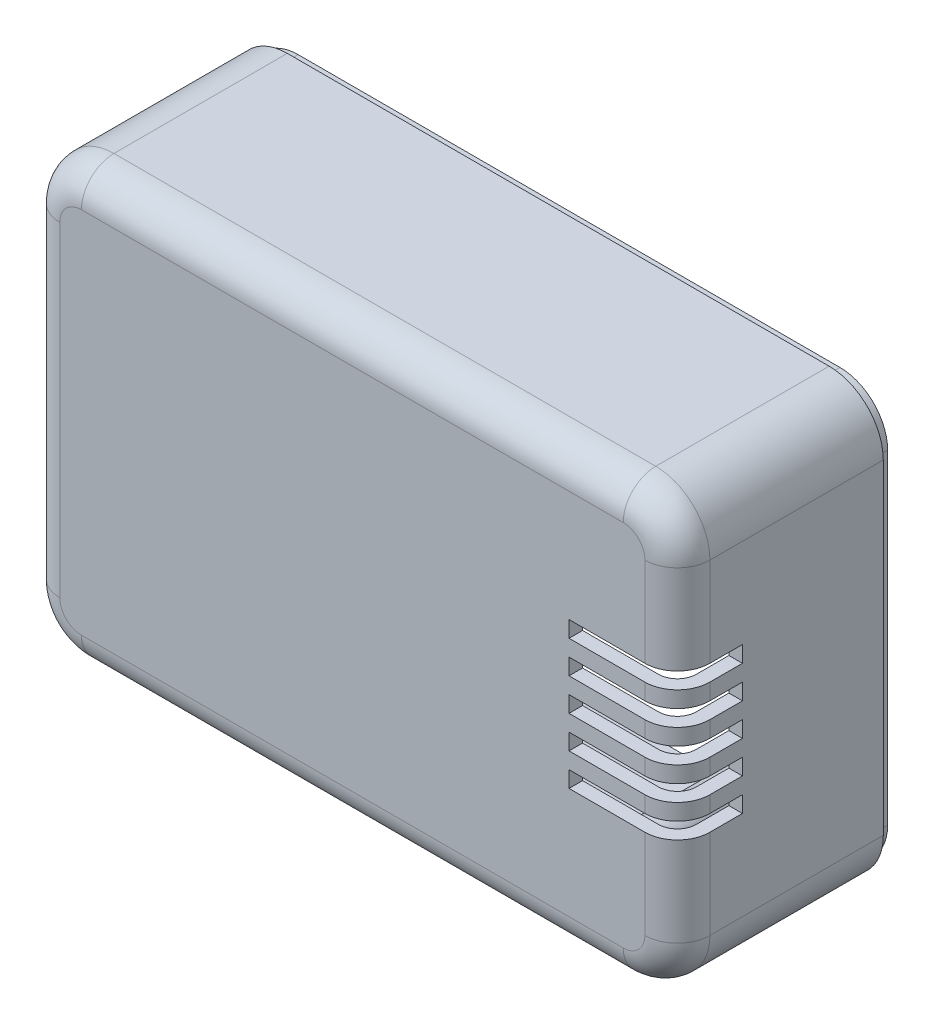
SolidWorks part; units mm, degrees
ref_plane "前视基准面" through (0, 0, 0) normal (0, 0, 1) x (1, 0, 0)
ref_plane "上视基准面" through (0, 0, 0) normal (0, 1, 0) x (1, 0, 0)
ref_plane "右视基准面" through (0, 0, 0) normal (1, 0, 0) x (0, 0, -1)
sketch "草图1" plane through (0, 0, 0) normal (0, 0, 1) x (1, 0, 0)
  line L0 (-50, -40) -> (50, -40)
  line L1 (60, -30) -> (60, 30)
  line L2 (50, 40) -> (-50, 40)
  line L3 (-60, 30) -> (-60, -30)
  arc A0 (-60, -30) -> (-50, -40) centre (-50, -30) ccw
  arc A1 (50, -40) -> (60, -30) centre (50, -30) ccw
  arc A2 (60, 30) -> (50, 40) centre (50, 30) ccw
  arc A3 (-50, 40) -> (-60, 30) centre (-50, 30) ccw
extrude "凸台-拉伸1" add sketch "草图1" along normal blind 40
fillet "圆角1" radius 6 8 edges at (57.0711, -37.0711, 40) (-57.0711, -37.0711, 40) (-57.0711, 37.0711, 40) (57.0711, 37.0711, 40) (0, -40, 40) (0, 40, 40) (-60, 0, 40) (60, 0, 40)
shell "抽壳2" thickness 2.5
sketch "草图2" plane through (0, 0, 0) normal (0, 0, 1) x (1, 0, 0)
  line L0 (-50, -40) -> (50, -40)
  line L1 (60, -30) -> (60, 30)
  line L2 (50, 40) -> (-50, 40)
  line L3 (-60, 30) -> (-60, -30)
  line L4 (-50, -38.8) -> (50, -38.8)
  line L5 (58.8, -30) -> (58.8, 30)
  line L6 (50, 38.8) -> (-50, 38.8)
  line L7 (-58.8, 30) -> (-58.8, -30)
  arc A0 (-60, -30) -> (-50, -40) centre (-50, -30) ccw
  arc A1 (50, -40) -> (60, -30) centre (50, -30) ccw
  arc A2 (60, 30) -> (50, 40) centre (50, 30) ccw
  arc A3 (-50, 40) -> (-60, 30) centre (-50, 30) ccw
  arc A4 (-58.8, -30) -> (-50, -38.8) centre (-50, -30) ccw
  arc A5 (50, -38.8) -> (58.8, -30) centre (50, -30) ccw
  arc A6 (58.8, 30) -> (50, 38.8) centre (50, 30) ccw
  arc A7 (-50, 38.8) -> (-58.8, 30) centre (-50, 30) ccw
extrude "切除-拉伸1" cut sketch "草图2" along normal blind 2
ref_plane "基准面1" through (0, -12, 0) normal (0, 1, 0) x (1, 0, 0)
sketch "草图3" plane through (0, -12, 0) normal (0, 1, 0) x (1, 0, 0)
  line L0 (40, -28) -> (61, -28)
  line L1 (61, -28) -> (61, -41)
  line L2 (61, -41) -> (40, -41)
  line L3 (40, -41) -> (40, -28)
extrude "切除-拉伸2" cut sketch "草图3" against normal mid plane 3
pattern_linear "阵列(线性)1" count 5 spacing 6 along (0, 1, 0) of "切除-拉伸2"
ref_plane "基准面2" through (0, 0, 5) normal (0, 0, 1) x (1, 0, 0)
sketch "草图4" plane through (0, 0, 5) normal (0, 0, 1) x (1, 0, 0)
  circle A0 centre (-45, -25) radius 4
  circle A1 centre (-45, 25) radius 4
  circle A2 centre (45, -25) radius 4
  circle A3 centre (45, 25) radius 4
extrude "凸台-拉伸2" add sketch "草图4" along normal blind 32.5
sketch "草图5" plane through (0, 0, 5) normal (0, 0, 1) x (1, 0, 0)
  circle A0 centre (-45, -25) radius 1.25
  circle A1 centre (-45, 25) radius 1.25
  circle A2 centre (45, -25) radius 1.25
  circle A3 centre (45, 25) radius 1.25
extrude "切除-拉伸3" cut sketch "草图5" along normal blind 12
